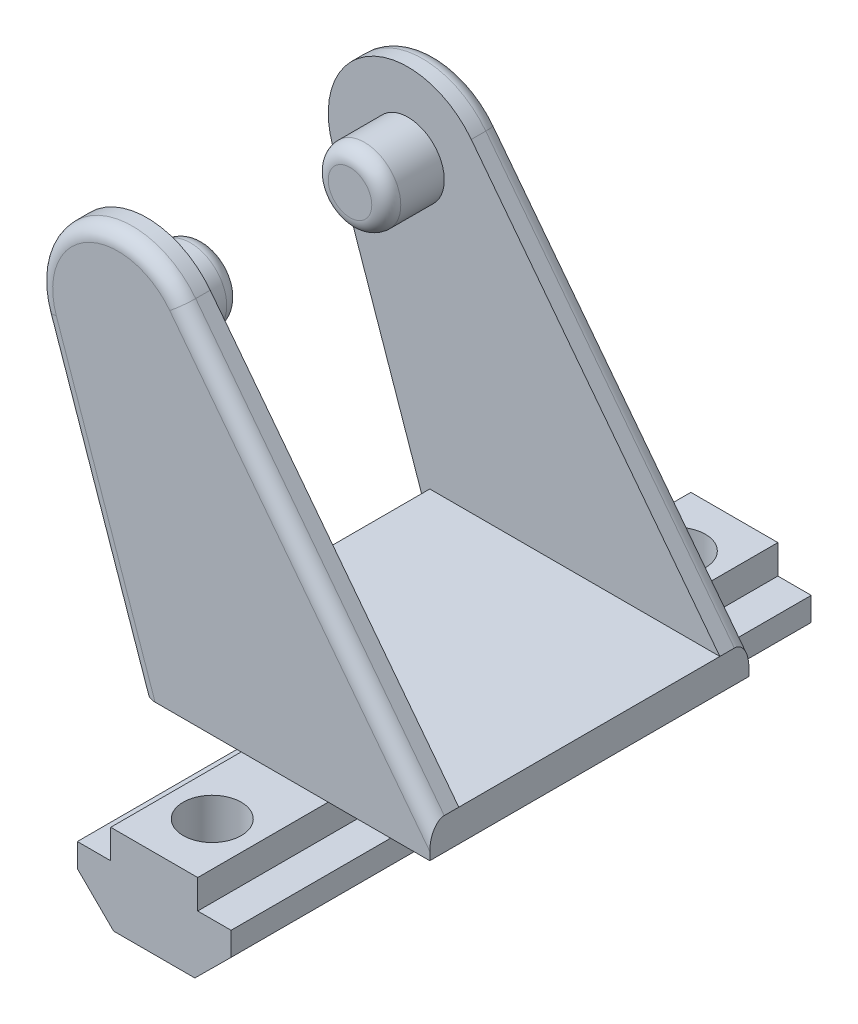
SolidWorks part; units mm, degrees
ref_plane "Front (XY)" through (0, 0, 0) normal (0, 0, 1) x (1, 0, 0)
ref_plane "Top (XZ)" through (0, 0, 0) normal (0, 1, 0) x (1, 0, 0)
ref_plane "Right (YZ)" through (0, 0, 0) normal (1, 0, 0) x (0, 0, -1)
sketch "Sketch1" plane through (0, 0, 0) normal (0, 0, 1) x (1, 0, 0)
  line L0 (0, -6.1) -> (0, 0) construction
  line L1 (-3, 0) -> (3, 0)
  line L2 (-3, 0) -> (-3, -2)
  line L3 (3, 0) -> (3, -2)
  line L4 (-3, -2) -> (-5.3, -2)
  line L5 (3, -2) -> (5.3, -2)
  line L6 (-5.3, -2) -> (-5.3, -3.62)
  line L7 (5.3, -2) -> (5.3, -3.62)
  line L8 (-2.8, -6.1) -> (2.8, -6.1)
  line L9 (-2.8, -6.1) -> (-5.3, -3.62)
  line L10 (2.8, -6.1) -> (5.3, -3.62)
  point P4 (0, 0)
  point P13 (0, -6.1)
  dimension "D1" = 6
  dimension "D2" = 6.1
  dimension "D3" = 2.3
  dimension "D4" = 4.1
  dimension "D5" = 3.5214
  dimension "D6" = 1.62
extrude "Boss-Extrude1" add sketch "Sketch1" along normal mid plane 40
sketch "Sketch2" plane through (0, 0, 0) normal (0, 1, 0) x (1, 0, 0)
  line L0 (-10, 11) -> (10, 11)
  line L1 (10, 11) -> (10, -11)
  line L2 (10, -11) -> (-10, -11)
  line L3 (-10, -11) -> (-10, 11)
  point P3 (0, 11)
  point P6 (-10, 0)
  dimension "D1" = 20
  dimension "D2" = 22
extrude "Boss-Extrude2" add sketch "Sketch2" along normal blind 2.2
sketch "Sketch3" plane through (0, 0, 0) normal (0, 0, 1) x (1, 0, 0)
  line L3 (-10, 2.2) -> (-10, 0) construction
  line L10 (0, 0) -> (-11.5, 0) construction
  line L11 (-11.5, 0) -> (-11.5, 21.15) construction
  circle A0 centre (-11.5, 21.15) radius 2.5 construction
  dimension "D3" = 5
  dimension "D1" = 11.5
  dimension "D2" = 21.15
sketch "Sketch4" plane through (0, 0, 11) normal (0, 0, 1) x (1, 0, 0)
  line L0 (-3, 0) -> (3, 0) construction
  line L2 (-10, 0) -> (-3, 0) construction
  line L3 (10, 2.2) -> (10, 0) construction
  line L4 (3, 0) -> (10, 0) construction
  line L5 (-3, 0) -> (3, 0)
  line L7 (-10, 0) -> (-3, 0)
  line L8 (10, 2.2) -> (10, 0)
  line L9 (3, 0) -> (10, 0)
  line L10 (-10, 0) -> (-16.6975, 19.3511)
  line L11 (10, 2.2) -> (-7.1391, 24.5015)
  circle A2 centre (-11.5, 21.15) radius 5.5
  arc A3 (-7.1391, 24.5015) -> (-16.6975, 19.3511) centre (-11.5, 21.15) ccw
  dimension "D1" = 3
extrude "Boss-Extrude3" add sketch "Sketch4" against normal blind 2
sketch "Sketch5" plane through (0, 0, 9) normal (0, 0, -1) x (-1, 0, 0)
  circle A0 centre (11.5, 21.15) radius 2.5 construction
  circle A1 centre (11.5, 21.15) radius 2.5
extrude "Boss-Extrude4" add sketch "Sketch5" along normal blind 4
fillet "Fillet1" radius 1 1 edges at (-14, 21.15, 5)
fillet "Fillet2" radius 1 3 edges at (1.4305, 13.3507, 11) (-14.1089, 25.9919, 11) (-13.3488, 9.6756, 11)
mirror "Mirror1" about plane through (0, 0, 0) normal (0, 0, 1) of "Fillet2", "Boss-Extrude4", "Fillet1", "Boss-Extrude3"
sketch "Sketch6" plane through (0, 0, 0) normal (0, 1, 0) x (1, 0, 0)
  circle A0 centre (0, 16) radius 2
  circle A1 centre (0, -16) radius 2
  dimension "D1" = 4
  dimension "D2" = 16
  dimension "D3" = 16
extrude "Cut-Extrude1" cut sketch "Sketch6" against normal through all
